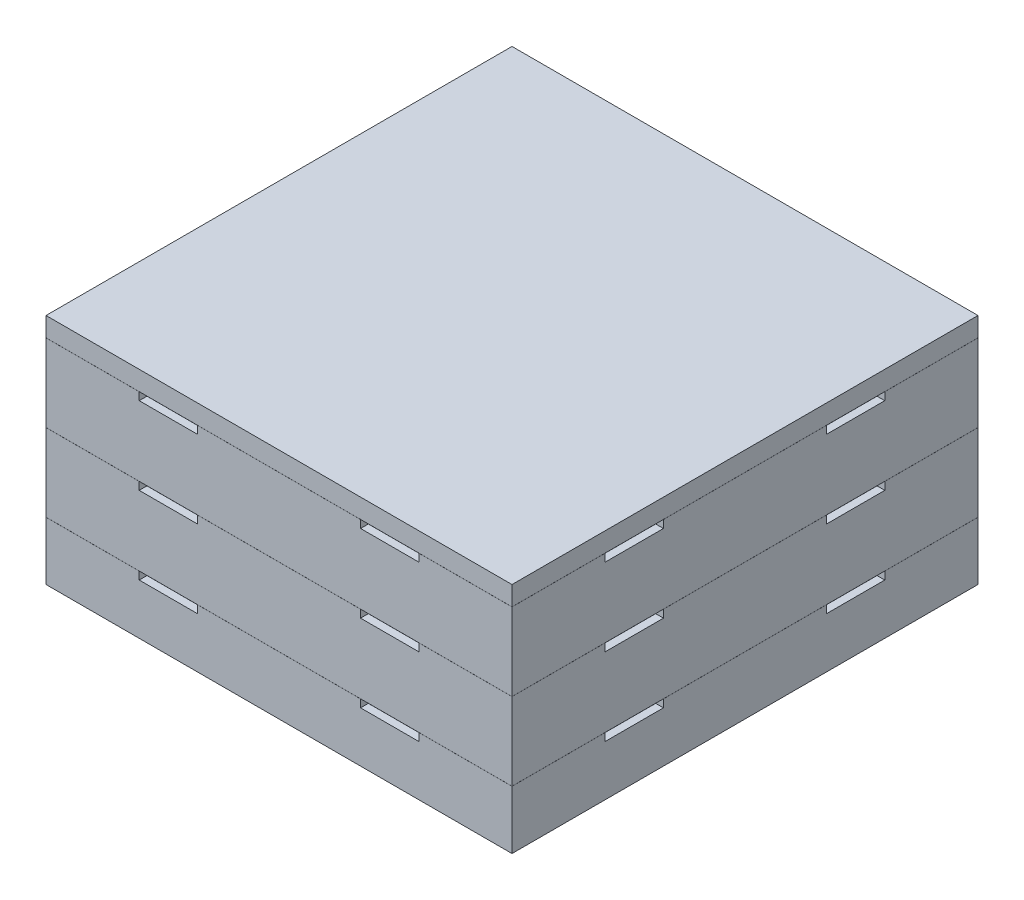
SolidWorks part; units mm, degrees
ref_plane "前视基准面" through (0, 0, 0) normal (0, 0, 1) x (1, 0, 0)
ref_plane "上视基准面" through (0, 0, 0) normal (0, 1, 0) x (1, 0, 0)
ref_plane "右视基准面" through (0, 0, 0) normal (1, 0, 0) x (0, 0, -1)
other "Configuration Table"
sketch "草图1" plane through (0, 0, 0) normal (0, 1, 0) x (1, 0, 0)
  line L5 (0, 0) -> (-600, 0)
  line L6 (0, 0) -> (0, -600)
  line L7 (0, -600) -> (-600, -600)
  line L8 (-600, 0) -> (-600, -600)
  dimension "D1" = 600
extrude "凸台-拉伸1" add sketch "草图1" along normal blind 600
sketch "草图2" plane through (-600, 0, 0) normal (-1, 0, 0) x (0, 0, 1)
  line L0 (600, 150.2) -> (0, 150.2)
  line L1 (600, 600) -> (600, 0) construction
  line L2 (0, 600) -> (0, 0) construction
  line L3 (0, 150.2) -> (0, 150)
  line L4 (0, 150) -> (210, 150)
  line L5 (210, 150) -> (210, 130)
  line L6 (210, 130) -> (360, 130)
  line L7 (360, 130) -> (360, 150)
  line L8 (360, 150) -> (600, 150)
  line L13 (600, 150) -> (600, 150.2)
  line L14 (0, 0) -> (600, 0) construction
  dimension "D1" = 0.2
  dimension "D2" = 20
  dimension "D3" = 150
  dimension "D4" = 240
  dimension "D5" = 210
  dimension "D6" = 150
extrude "切除-拉伸1" cut sketch "草图2" against normal blind 20
sketch "草图3" plane through (0, 0, 600) normal (0, 0, 1) x (1, 0, 0)
  line L0 (-580, 150.2) -> (-580, 150)
  line L1 (-580, 150) -> (-360, 150)
  line L2 (-360, 150) -> (-360, 130)
  line L3 (-360, 130) -> (-210, 130)
  line L4 (-210, 130) -> (-210, 150)
  line L5 (-210, 150) -> (0, 150)
  line L6 (0, 600) -> (0, 0) construction
  line L7 (0, 150) -> (0, 150.2)
  line L8 (0, 150.2) -> (-580, 150.2)
  line L9 (-600, 150) -> (-600, 0) construction
  dimension "D1" = 20
  dimension "D2" = 150
  dimension "D3" = 240
extrude "切除-拉伸2" cut sketch "草图3" against normal blind 20
pattern_linear "阵列(线性)1" count 3 spacing 200 along (0, 1, 0) of "切除-拉伸1", "切除-拉伸2"
mirror "镜向1" about plane through (0, 600, 0) normal (0, 0, 1) of bodies 111 108
mirror "镜向2" about plane through (0, 600, 0) normal (-1, 0, 0) of bodies 109
